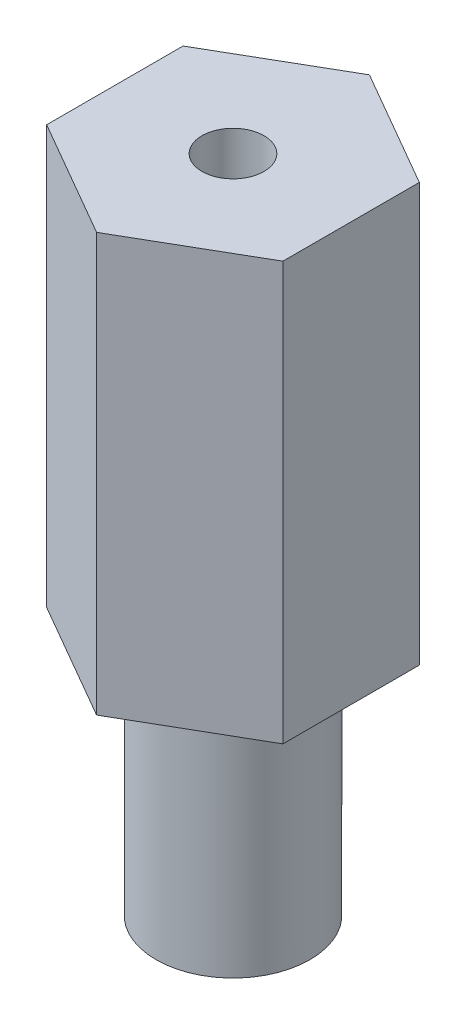
SolidWorks part; units mm, degrees
material "6061-T6 (SS)"
ref_plane "Front Plane" through (0, 0, 0) normal (0, 0, 1) x (1, 0, 0)
ref_plane "Top Plane" through (0, 0, 0) normal (0, 1, 0) x (1, 0, 0)
ref_plane "Right Plane" through (0, 0, 0) normal (1, 0, 0) x (0, 0, -1)
sketch "Sketch1" plane through (0, 0, 0) normal (0, 1, 0) x (1, 0, 0)
  line L1 (2.2606, 1.3052) -> (0, 2.6103)
  line L2 (0, 2.6103) -> (-2.2606, 1.3052)
  line L3 (-2.2606, 1.3052) -> (-2.2606, -1.3052)
  line L4 (-2.2606, -1.3052) -> (0, -2.6103)
  line L5 (0, -2.6103) -> (2.2606, -1.3052)
  line L6 (2.2606, -1.3052) -> (2.2606, 1.3052)
  circle A0 centre (0, 0) radius 2.2606 construction
  dimension "D1" = 4.5212
extrude "Boss-Extrude1" add sketch "Sketch1" along normal blind 8
sketch "Sketch2" plane through (0, 0, 0) normal (0, -1, 0) x (1, 0, 0)
  circle A0 centre (0, 0) radius 1.4732
  dimension "D1" = 2.9464
extrude "Boss-Extrude2" add sketch "Sketch2" along normal blind 4.6228
sketch "Sketch3" plane through (0, 8, 0) normal (0, 1, 0) x (1, 0, 0)
  circle A0 centre (0, 0) radius 0.5937
extrude "Cut-Extrude1" cut sketch "Sketch3" against normal blind 2.54
